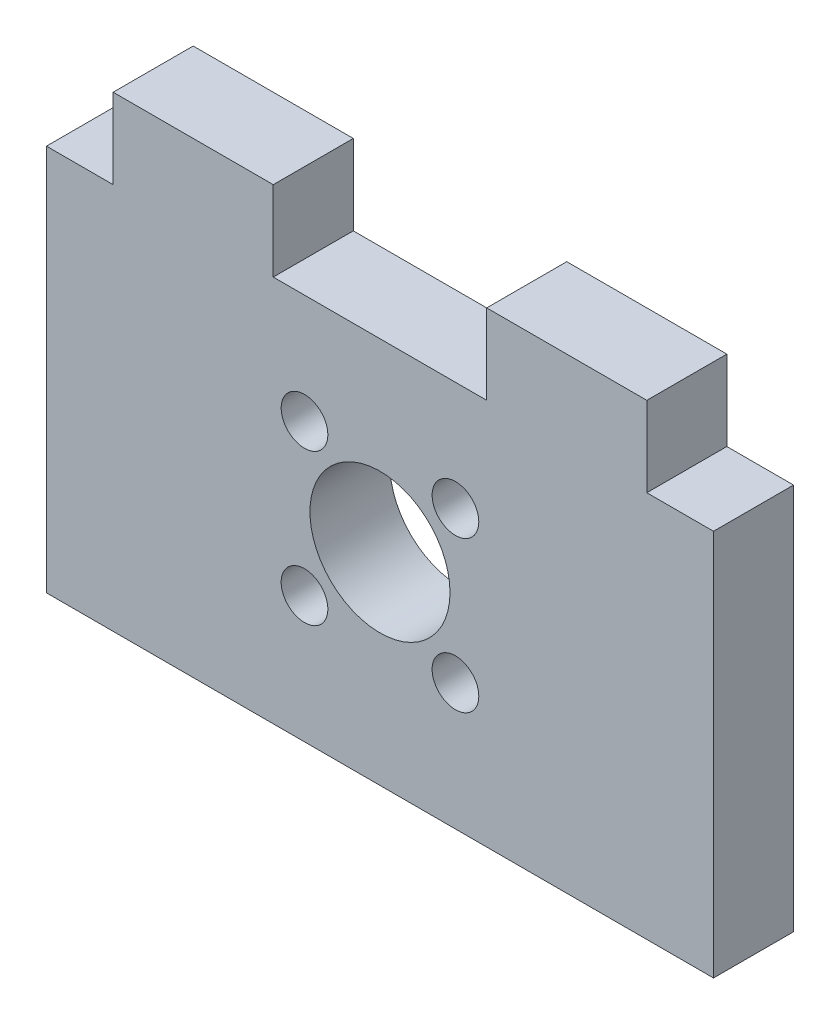
SolidWorks part; units mm, degrees
ref_plane "Plano frontal" through (0, 0, 0) normal (0, 0, 1) x (1, 0, 0)
ref_plane "Plano superior" through (0, 0, 0) normal (0, 1, 0) x (1, 0, 0)
ref_plane "Plano direito" through (0, 0, 0) normal (1, 0, 0) x (0, 0, -1)
sketch "Esboço1" plane through (0, 0, 0) normal (0, 0, 1) x (1, 0, 0)
  line L0 (0, -17.5) -> (0, -2.35) construction
  line L1 (-25, 17.5) -> (25, 17.5)
  line L2 (-25, 17.5) -> (-25, -17.5)
  line L3 (-25, -17.5) -> (25, -17.5)
  line L4 (25, 17.5) -> (25, -17.5)
  line L5 (-25, 17.5) -> (25, -17.5) construction
  line L6 (-25, -17.5) -> (25, 17.5) construction
  line L7 (-8, -2.35) -> (8, -2.35) construction
  line L9 (-5.6569, -8.0069) -> (5.6569, -8.0069) construction
  line L10 (-5.6569, -8.0069) -> (-5.6569, 3.3069) construction
  line L11 (-5.6569, 3.3069) -> (5.6569, 3.3069) construction
  line L12 (5.6569, -8.0069) -> (5.6569, 3.3069) construction
  line L13 (-5.6569, -8.0069) -> (5.6569, 3.3069) construction
  line L14 (-5.6569, 3.3069) -> (5.6569, -8.0069) construction
  circle A0 centre (0, -2.35) radius 5.25
  circle A2 centre (5.6569, 3.3069) radius 1.75
  circle A3 centre (-5.6569, 3.3069) radius 1.75
  circle A4 centre (-5.6569, -8.0069) radius 1.75
  circle A5 centre (5.6569, -8.0069) radius 1.75
  point P0 (0, 0)
  point P23 (0, -7.5)
  point P24 (0, 0.15)
  point P25 (0, -4.85)
  dimension "D4" = 10.5
  dimension "D5" = 16
  dimension "D7" = 3.5
  dimension "D1" = 50
  dimension "D2" = 35
  dimension "D3" = 19.85
extrude "Ressalto-extrusão1" add sketch "Esboço1" along normal blind 6
sketch "Esboço2" plane through (0, 0, 6) normal (0, 0, 1) x (1, 0, 0)
  line L0 (-8, 17.5) -> (-8, 11.5)
  line L1 (-25, 17.5) -> (-20, 17.5)
  line L2 (25, 11.5) -> (-25, 11.5)
  line L3 (25, 11.5) -> (-25, 11.5) construction
  line L4 (-25, 17.5) -> (-25, 11.5)
  line L5 (-25, 11.5) -> (-20, 11.5)
  line L6 (-20, 17.5) -> (-20, 11.5)
  line L7 (25, 17.5) -> (20, 17.5)
  line L8 (-20, 17.5) -> (-20, -17.5)
  line L9 (-20, 17.5) -> (-20, -17.5) construction
  line L10 (25, 17.5) -> (25, 11.5)
  line L11 (20, -17.5) -> (20, 17.5)
  line L12 (20, -17.5) -> (20, 17.5) construction
  line L13 (25, 11.5) -> (20, 11.5)
  line L14 (20, 17.5) -> (20, 11.5)
  line L15 (25, 17.5) -> (-25, 17.5) construction
  line L16 (-8, 11.5) -> (8, 11.5)
  line L17 (8, 11.5) -> (8, 17.5)
  line L18 (0, 11.5) -> (0, 17.5) construction
  line L19 (0, -17.5) -> (0, 17.5) construction
  line L20 (-25, -17.5) -> (25, -17.5) construction
  line L21 (-8, 17.5) -> (8, 17.5)
  dimension "D4" = 12
  dimension "D1" = 6
  dimension "D2" = 5
  dimension "D3" = 5
extrude "Corte-extrusão1" cut sketch "Esboço2" against normal up to surface (6 mm away) up to face at (0, 0, 0)
ref_plane "Plano1" through (0, 0, 0) normal (-1, 0, 0) x (0, 0, 1)
ref_plane "Plano2" through (0, 0, 3) normal (0, 0, -1) x (-1, 0, 0)
